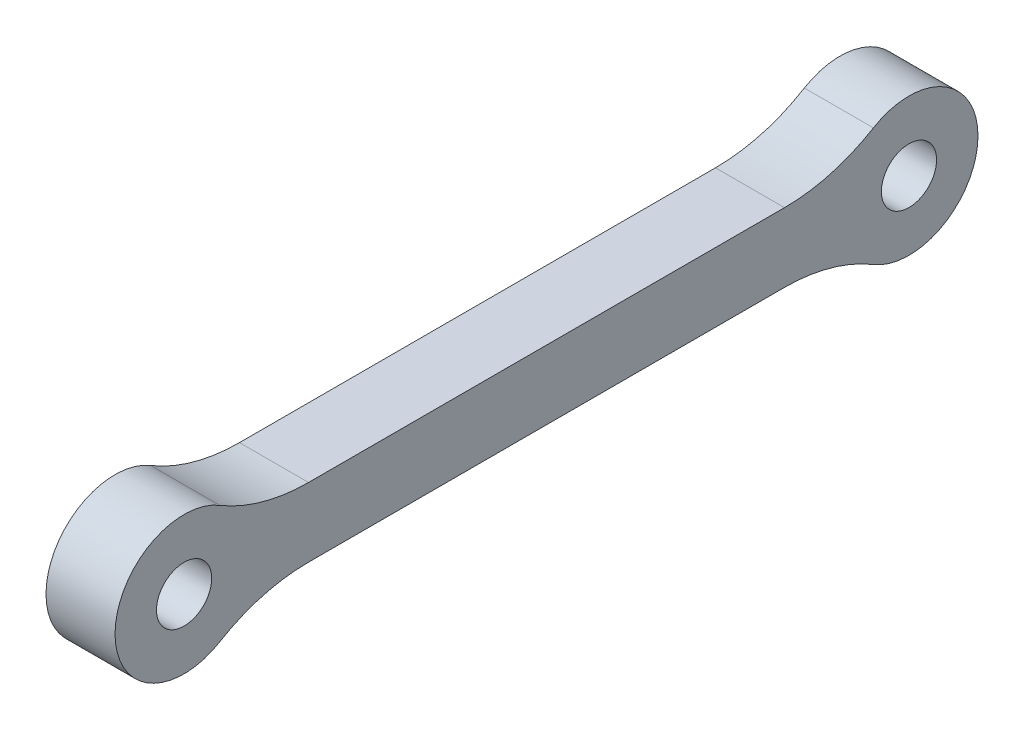
SolidWorks part; units mm, degrees
material "Tough 2000"
ref_plane "Front Plane" through (0, 0, 0) normal (0, 0, 1) x (1, 0, 0)
ref_plane "Top Plane" through (0, 0, 0) normal (0, 1, 0) x (1, 0, 0)
ref_plane "Right Plane" through (0, 0, 0) normal (1, 0, 0) x (0, 0, -1)
sketch "Sketch1" plane through (0, 0, 0) normal (1, 0, 0) x (0, 0, -1)
  line L2 (21, 2) -> (38.5359, 2)
  line L3 (21, 2) -> (3.4641, 2)
  line L5 (21, -2) -> (38.5359, -2)
  line L6 (21, -2) -> (3.4641, -2)
  arc A0 (38.5359, -2) -> (38.5359, 2) centre (42, 0) ccw
  arc A1 (3.4641, 2) -> (3.4641, -2) centre (0, 0) ccw
  circle A2 centre (0, 0) radius 1.6
  circle A3 centre (42, 0) radius 1.6
extrude "Boss-Extrude1" add sketch "Sketch1" along normal blind 4
fillet "Fillet1" radius 10 4 edges at (2, 2, -3.4641) (2, -2, -3.4641) (2, -2, -38.5359) (2, 2, -38.5359)
